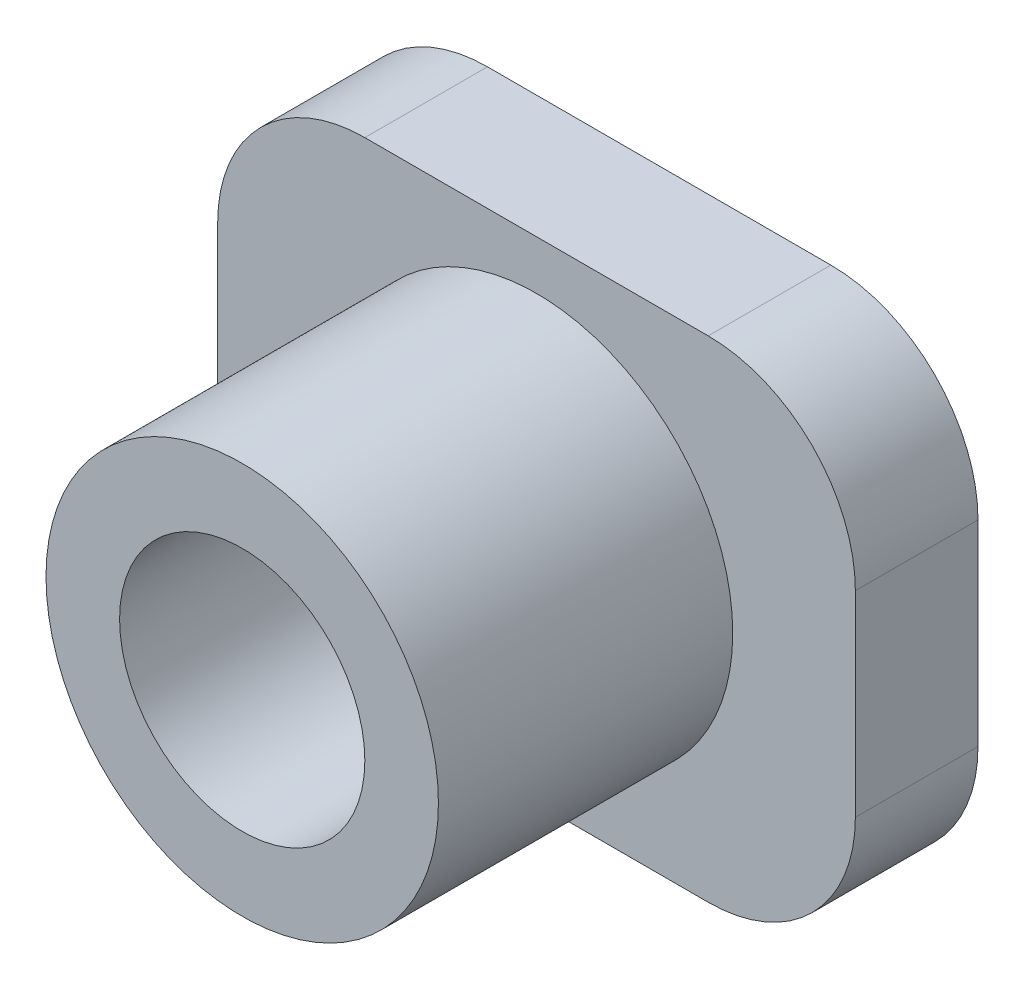
SolidWorks part; units mm, degrees
ref_plane "前视基准面" through (0, 0, 0) normal (0, 0, 1) x (1, 0, 0)
ref_plane "上视基准面" through (0, 0, 0) normal (0, 1, 0) x (1, 0, 0)
ref_plane "右视基准面" through (0, 0, 0) normal (1, 0, 0) x (0, 0, -1)
sketch "草图1" plane through (0, 0, 0) normal (0, 0, 1) x (1, 0, 0)
  line L0 (-98.2536, 0) -> (119.8694, 0) construction
  line L1 (0, 79.5854) -> (0, -81.1575) construction
  line L2 (-13, -10) -> (-13, 10)
  line L3 (-13, 10) -> (13, 10)
  line L4 (13, -10) -> (13, 10)
  line L5 (-13, -10) -> (13, -10)
  point P9 (0, 10)
  point P11 (13, 0)
  point P12 (-13, 0)
  dimension "D1" = 10
  dimension "D2" = 13
extrude "凸台-拉伸1" add sketch "草图1" along normal blind 5
sketch "草图2" plane through (0, 0, 5) normal (0, 0, 1) x (1, 0, 0)
  circle A0 centre (0, 0) radius 8
  circle A1 centre (0, 0) radius 5
  dimension "D1" = 16
  dimension "D2" = 10
extrude "凸台-拉伸2" add sketch "草图2" along normal blind 12
cosmetic thread "装饰螺纹线1" parameters "D1"=10, "D2"=12
fillet "圆角1" radius 6 4 edges at (13, -10, 2.5) (13, 10, 2.5) (-13, -10, 2.5) (-13, 10, 2.5)
